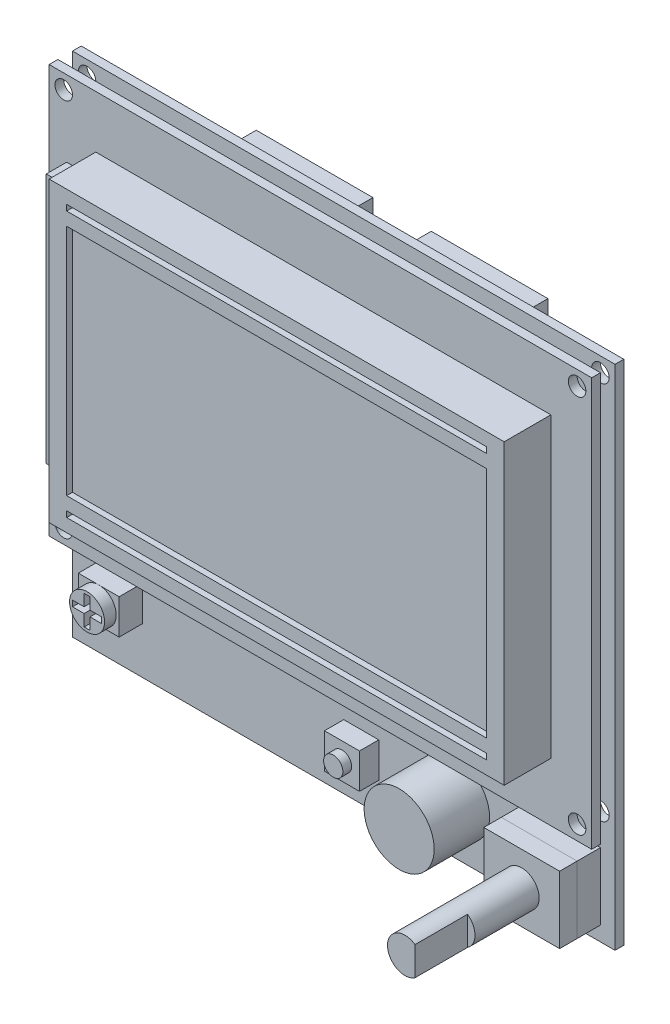
SolidWorks part; units mm, degrees
material "7075-T6 (SN)"
ref_plane "Plan de face" through (0, 0, 0) normal (0, 0, 1) x (1, 0, 0)
ref_plane "Plan de dessus" through (0, 0, 0) normal (0, 1, 0) x (1, 0, 0)
ref_plane "Plan de droite" through (0, 0, 0) normal (1, 0, 0) x (0, 0, -1)
sketch "Esquisse1" plane through (0, 0, 0) normal (0, 0, 1) x (1, 0, 0)
  line L1 (-39, 0) -> (39, 0)
  line L2 (-39, 0) -> (-39, 51)
  line L3 (-39, 51) -> (39, 51)
  line L4 (39, 0) -> (39, 51)
  dimension "D1" = 78
  dimension "D2" = 51
extrude "Boss.-Extru.1" add sketch "Esquisse1" along normal blind 8
sketch "Esquisse2" plane through (0, 0, 8) normal (0, 0, 1) x (1, 0, 0)
  line L0 (39, 51) -> (-39, 51) construction
  line L1 (-36, 45.5) -> (36, 45.5)
  line L2 (-36, 45.5) -> (-36, 5.5)
  line L3 (-36, 5.5) -> (36, 5.5)
  line L4 (36, 45.5) -> (36, 5.5)
  line L5 (36, 3.25) -> (-36, 3.25)
  line L6 (36, 3.25) -> (36, 2.25)
  line L7 (36, 2.25) -> (-36, 2.25)
  line L8 (-36, 3.25) -> (-36, 2.25)
  line L9 (-36, 47.75) -> (36, 47.75)
  line L10 (-36, 47.75) -> (-36, 48.75)
  line L11 (-36, 48.75) -> (36, 48.75)
  line L12 (36, 47.75) -> (36, 48.75)
  line L13 (0, 51) -> (0, 0) construction
  line L14 (-39, 25.5) -> (39, 25.5) construction
  line L15 (-39, 51) -> (-39, 0) construction
  line L16 (39, 0) -> (39, 51) construction
  dimension "D1" = 40
  dimension "D2" = 1
  dimension "D3" = 2.25
  dimension "D4" = 51
  dimension "D5" = 72
  dimension "D6" = 78
  dimension "D7" = 3
  dimension "D8" = 2.25
  dimension "D9" = 2.25
extrude "Enlèv. mat.-Extru.1" cut sketch "Esquisse2" against normal blind 1
sketch "Esquisse3" plane through (0, 0, 0) normal (0, 0, -1) x (-1, 0, 0)
  line L0 (39, 25.5) -> (44, 25.5) construction
  line L1 (39, 51) -> (39, 0) construction
  line L3 (39, 47) -> (44, 47)
  line L4 (39, 47) -> (39, 4)
  line L5 (39, 4) -> (44, 4)
  line L6 (44, 47) -> (44, 4)
  dimension "D1" = 43
  dimension "D2" = 5
extrude "Boss.-Extru.2" add sketch "Esquisse3" against normal blind 3.5 separate body
sketch "Esquisse4" plane through (0, 0, 0) normal (0, 0, -1) x (-1, 0, 0)
  line L0 (-46, 25) -> (0.5, 25) construction
  line L1 (-46, 60) -> (47, 60)
  line L2 (-46, 60) -> (-46, -10)
  line L3 (-46, -10) -> (47, -10)
  line L4 (47, 60) -> (47, -10)
  line L5 (0.5, 25) -> (0.5, -10) construction
  line L6 (-39, 51) -> (39, 51) construction
  line L7 (-39, 0) -> (-39, 51) construction
  circle A0 centre (-43.5, 57.5) radius 1.5
  circle A1 centre (-43.5, -7.5) radius 1.5
  circle A2 centre (44.5, 57.5) radius 1.5
  circle A3 centre (44.5, -7.5) radius 1.5
  dimension "D3" = 3
  dimension "D1" = 93
  dimension "D2" = 70
  dimension "D4" = 2.5
  dimension "D5" = 2.5
  dimension "D6" = 9
  dimension "D7" = 7
extrude "Boss.-Extru.3" add sketch "Esquisse4" along normal blind 1.5 separate body
ref_plane "Plan1" through (0, 0, -4) normal (0, 0, -1) x (-1, 0, 0)
sketch "Esquisse5" plane through (0, 0, -4) normal (0, 0, -1) x (-1, 0, 0)
  line L1 (-46, 60) -> (47, 60)
  line L2 (-46, 60) -> (-46, -27)
  line L3 (-46, -27) -> (47, -27)
  line L4 (47, 60) -> (47, -27)
  circle A0 centre (-43.5, 57.5) radius 1.5
  circle A1 centre (-43.5, -7.5) radius 1.5
  circle A2 centre (44.5, -7.5) radius 1.5
  circle A3 centre (44.5, 57.5) radius 1.5
  dimension "D1" = 87
extrude "Boss.-Extru.4" add sketch "Esquisse5" along normal blind 1.5 separate body
sketch "Esquisse6" plane through (-47, 0, 0) normal (-1, 0, 0) x (0, 0, 1)
  line L0 (-5.5, 38.5) -> (-8.5, 38.5)
  line L1 (-5.5, -27) -> (-5.5, 60) construction
  line L2 (-8.5, 38.5) -> (-8.5, 12)
  line L3 (-8.5, 12) -> (-5.5, 12)
  line L4 (-5.5, 60) -> (-4, 60) construction
  line L5 (-5.5, 38.25) -> (-8.25, 38.25)
  line L6 (-8.25, 38.25) -> (-8.25, 12.25)
  line L7 (-8.25, 12.25) -> (-5.5, 12.25)
  line L8 (-5.5, 38.5) -> (-5.5, 38.25)
  line L9 (-5.5, 12.25) -> (-5.5, 12)
  dimension "D1" = 21.5
  dimension "D2" = 26.5
  dimension "D3" = 3
  dimension "D4" = 0.25
extrude "Boss.-Extru.5" add sketch "Esquisse6" against normal blind 25 separate body
sketch "Esquisse7" plane through (0, 0, -5.5) normal (0, 0, -1) x (-1, 0, 0)
  line L0 (47, -27) -> (47, 60) construction
  line L1 (26, 53.5) -> (6, 53.5)
  line L2 (26, 53.5) -> (26, 44.5)
  line L3 (26, 44.5) -> (6, 44.5)
  line L4 (6, 53.5) -> (6, 44.5)
  line L5 (-24, 53.5) -> (-4, 53.5)
  line L6 (-24, 53.5) -> (-24, 44.5)
  line L7 (-24, 44.5) -> (-4, 44.5)
  line L8 (-4, 53.5) -> (-4, 44.5)
  line L9 (47, 60) -> (-46, 60) construction
  line L10 (-23, 52.5) -> (-5, 52.5)
  line L11 (-5, 52.5) -> (-5, 45.5)
  line L12 (-23, 45.5) -> (-5, 45.5)
  line L13 (-23, 52.5) -> (-23, 45.5)
  line L14 (25, 52.5) -> (7, 52.5)
  line L15 (7, 52.5) -> (7, 45.5)
  line L16 (25, 45.5) -> (7, 45.5)
  line L17 (25, 52.5) -> (25, 45.5)
  dimension "D1" = 20
  dimension "D2" = 9
  dimension "D3" = 10
  dimension "D4" = 21
  dimension "D5" = 6.5
  dimension "D6" = 1
extrude "Boss.-Extru.6" add sketch "Esquisse7" along normal blind 9 separate body
sketch "Esquisse8" plane through (0, 0, -4) normal (0, 0, 1) x (1, 0, 0)
  line L0 (46, -27) -> (-47, -27) construction
  line L1 (30.5, -13) -> (43.5, -13)
  line L2 (30.5, -13) -> (30.5, -24.5)
  line L3 (30.5, -24.5) -> (43.5, -24.5)
  line L4 (43.5, -13) -> (43.5, -24.5)
  line L5 (46, 60) -> (46, -27) construction
  line L6 (-47, -27) -> (-47, 60) construction
  line L7 (-42, -13) -> (-35, -13)
  line L8 (-42, -13) -> (-42, -19)
  line L9 (-42, -19) -> (-35, -19)
  line L10 (-35, -13) -> (-35, -19)
  dimension "D1" = 11.5
  dimension "D2" = 13
  dimension "D3" = 2.5
  dimension "D4" = 2.5
  dimension "D5" = 6
  dimension "D6" = 7
  dimension "D7" = 8
  dimension "D8" = 5
extrude "Boss.-Extru.7" add sketch "Esquisse8" along normal blind 4 separate body
sketch "Esquisse9" plane through (0, 0, 0) normal (0, 0, 1) x (1, 0, 0)
  line L0 (30.5, -24.5) -> (43.5, -24.5) construction
  line L1 (43.5, -13) -> (30.5, -13)
  line L2 (43.5, -13) -> (43.5, -24.5)
  line L3 (43.5, -24.5) -> (30.5, -24.5)
  line L4 (30.5, -13) -> (30.5, -24.5)
  line L5 (30.5, -13) -> (30.5, -24.5) construction
extrude "Boss.-Extru.8" add sketch "Esquisse9" along normal blind 3 separate body
sketch "Esquisse10" plane through (0, 0, 3) normal (0, 0, 1) x (1, 0, 0)
  circle A0 centre (37, -18.75) radius 3
  dimension "D1" = 6
extrude "Boss.-Extru.9" add sketch "Esquisse10" along normal blind 20 separate body
sketch "Esquisse11" plane through (0, 0, 23) normal (0, 0, 1) x (1, 0, 0)
  line L1 (38.7143, -16.288) -> (58.9108, -16.288)
  line L2 (38.7143, -16.288) -> (38.7143, -21.212)
  line L3 (38.7143, -21.212) -> (58.9108, -21.212)
  line L4 (58.9108, -16.288) -> (58.9108, -21.212)
  circle A0 centre (37, -18.75) radius 3 construction
extrude "Enlèv. mat.-Extru.2" cut sketch "Esquisse11" against normal blind 9
sketch "Esquisse12" plane through (0, 0, -4) normal (0, 0, 1) x (1, 0, 0)
  line L0 (46, -27) -> (-47, -27) construction
  line L1 (30.5, -13) -> (30.5, -24.5) construction
  circle A0 centre (18.5, -18) radius 6
  dimension "D1" = 12
  dimension "D2" = 9
  dimension "D3" = 12
extrude "Boss.-Extru.10" add sketch "Esquisse12" along normal blind 9.5 separate body
sketch "Esquisse13" plane through (0, 0, 0) normal (0, 0, 1) x (1, 0, 0)
  line L0 (-38, -13.5) -> (-39, -13.5)
  line L1 (-39, -13.5) -> (-39, -15.5)
  line L2 (-39, -15.5) -> (-41, -15.5)
  line L3 (-41, -15.5) -> (-41, -16.5)
  line L4 (-41, -16.5) -> (-39, -16.5)
  line L5 (-39, -16.5) -> (-39, -18.5)
  line L6 (-39, -18.5) -> (-38, -18.5)
  line L7 (-38, -18.5) -> (-38, -16.5)
  line L8 (-38, -16.5) -> (-36, -16.5)
  line L9 (-36, -16.5) -> (-36, -15.5)
  line L10 (-36, -15.5) -> (-38, -15.5)
  line L11 (-38, -15.5) -> (-38, -13.5)
  line L12 (-35, -19) -> (-42, -13) construction
  line L13 (-42, -13) -> (-42, -19) construction
  circle A0 centre (-38.5, -16) radius 3
  dimension "D1" = 1
  dimension "D2" = 2
  dimension "D3" = 0.5
  dimension "D4" = 0.5
extrude "Boss.-Extru.11" add sketch "Esquisse13" along normal blind 2 separate body
sketch "Esquisse14" plane through (0, 0, -4) normal (0, 0, 1) x (1, 0, 0)
  line L0 (46, -27) -> (-47, -27) construction
  line L1 (-0.5, -16) -> (5.5, -16)
  line L2 (-0.5, -16) -> (-0.5, -22)
  line L3 (-0.5, -22) -> (5.5, -22)
  line L4 (5.5, -16) -> (5.5, -22)
  line L5 (-47, -27) -> (-47, 60) construction
  dimension "D1" = 6
  dimension "D2" = 6
  dimension "D3" = 5
  dimension "D4" = 46.5
extrude "Boss.-Extru.12" add sketch "Esquisse14" along normal blind 3.3 separate body
sketch "Esquisse15" plane through (0, 0, -0.7) normal (0, 0, 1) x (1, 0, 0)
  line L0 (-0.5, -16) -> (5.5, -22) construction
  circle A0 centre (2.5, -19) radius 1.65
  dimension "D1" = 3.3
extrude "Boss.-Extru.13" add sketch "Esquisse15" along normal blind 1.5 separate body
sketch "Esboço1" plane through (0, 0, 8) normal (0, 0, 1) x (1, 0, 0)
  line L1 (-39, 51) -> (39, 51) construction
  line L2 (-39, 51) -> (-39, 0) construction
  line L3 (-39, 0) -> (39, 0) construction
  line L4 (39, 51) -> (39, 0) construction
  line L5 (-44.5, 57.5) -> (43.5, 57.5) construction
  line L6 (-44.5, 57.5) -> (-44.5, -7.5) construction
  line L7 (-44.5, -7.5) -> (43.5, -7.5) construction
  line L8 (43.5, 57.5) -> (43.5, -7.5) construction
  circle A0 centre (37, -18.75) radius 4.5
  circle A1 centre (2.5, -19) radius 3
  circle A2 centre (-38.5, -16) radius 5
  circle A3 centre (18.5, -18) radius 8
  dimension "D1" = 9
  dimension "D2" = 6
  dimension "D3" = 10
  dimension "D4" = 16
equation "\"D7@Esquisse2\"=(\"D6@Esquisse2\"-\"D5@Esquisse2\")/2"
equation "\"D8@Esquisse2\"=\"D3@Esquisse2\""
equation "\"D9@Esquisse2\"=\"D3@Esquisse2\""
equation "\"D3@Esquisse2\"=(\"D4@Esquisse2\"-\"D1@Esquisse2\"-(2*\"D2@Esquisse2\"))/4"
